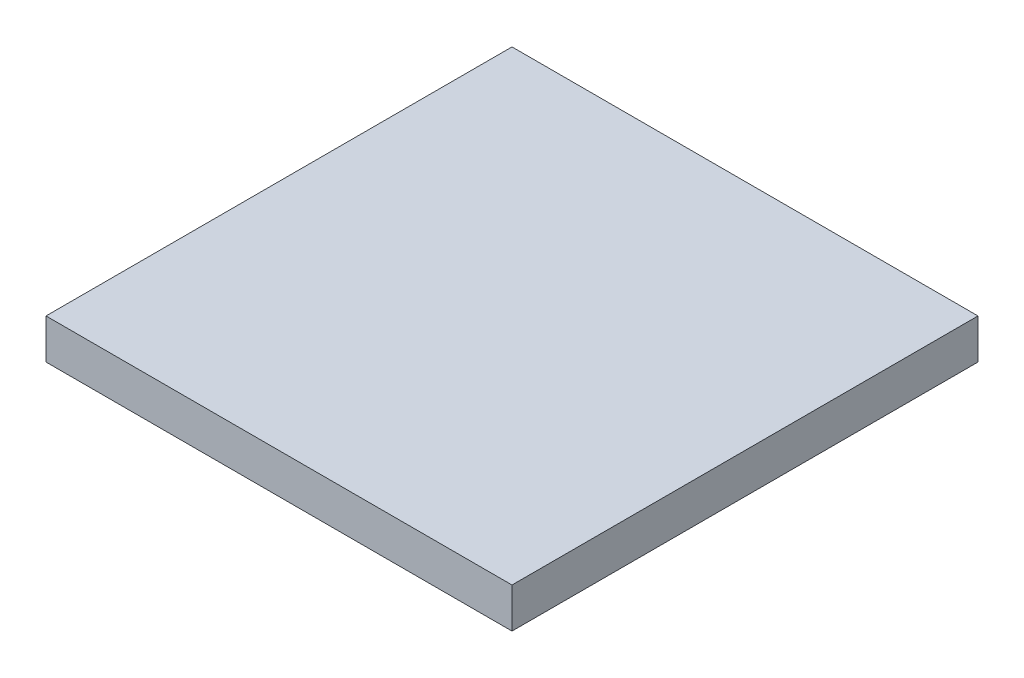
SolidWorks part; units mm, degrees
ref_plane "Front Plane" through (0, 0, 0) normal (0, 0, 1) x (1, 0, 0)
ref_plane "Top Plane" through (0, 0, 0) normal (0, 1, 0) x (1, 0, 0)
ref_plane "Right Plane" through (0, 0, 0) normal (1, 0, 0) x (0, 0, -1)
sketch "Sketch1" plane through (0, 0, 0) normal (0, 1, 0) x (1, 0, 0)
  line L1 (-58.8096, -14.2109) -> (-44.8096, -14.2109)
  line L2 (-58.8096, -14.2109) -> (-58.8096, -28.2109)
  line L3 (-58.8096, -28.2109) -> (-44.8096, -28.2109)
  line L4 (-44.8096, -14.2109) -> (-44.8096, -28.2109)
  line L5 (-58.8096, -14.2109) -> (-44.8096, -28.2109) construction
  line L6 (-58.8096, -28.2109) -> (-44.8096, -14.2109) construction
  point P0 (-51.8096, -21.2109)
  dimension "D1" = 14
  dimension "D2" = 14
extrude "Boss-Extrude1" add sketch "Sketch1" along normal blind 1.2 separate body
